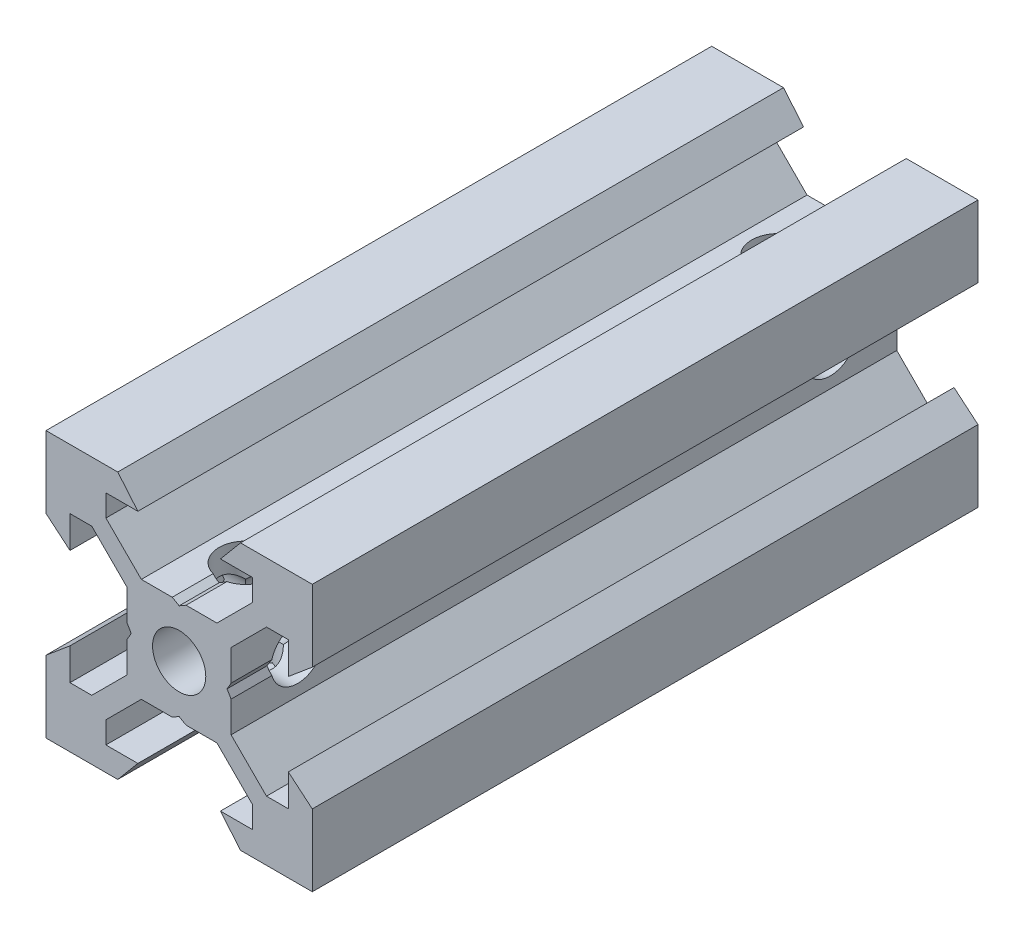
SolidWorks part; units mm, degrees
material "3.3535 (EN-AW 5754)"
ref_plane "Front Plane" through (0, 0, 0) normal (0, 0, 1) x (1, 0, 0)
ref_plane "Top Plane" through (0, 0, 0) normal (0, 1, 0) x (1, 0, 0)
ref_plane "Right Plane" through (0, 0, 0) normal (1, 0, 0) x (0, 0, -1)
sketch "Sketch1" plane through (0, 0, 0) normal (0, 0, 1) x (1, 0, 0)
  line L0 (10, 10) -> (4.6104, 10) construction
  line L1 (10, 10) -> (10, 4.6104) construction
  line L2 (10, -10) -> (10, -4.6104) construction
  line L3 (10, -10) -> (4.6104, -10) construction
  line L4 (10, 10) -> (10, 4.6104)
  line L5 (6.5607, 5.5) -> (8.2, 5.5)
  line L6 (5.5, 8.2) -> (5.5, 6.5607)
  line L7 (10, 10) -> (4.6104, 10)
  line L8 (10, 10) -> (10, 4.6104)
  line L9 (6.5607, 5.5) -> (3.9, 2.8393)
  line L10 (5.5, 6.5607) -> (2.8393, 3.9)
  line L11 (10, 4.6104) -> (8.2, 3.1)
  line L12 (4.6104, 10) -> (3.1, 8.2)
  line L13 (8.2, 3.1) -> (8.2, 5.5)
  line L14 (3.1, 8.2) -> (5.5, 8.2)
  line L15 (-6.5607, 5.5) -> (-8.2, 5.5)
  line L16 (6.5607, -5.5) -> (8.2, -5.5)
  line L17 (3.1, -8.2) -> (5.5, -8.2)
  line L18 (8.2, -3.1) -> (8.2, -5.5)
  line L19 (4.6104, -10) -> (3.1, -8.2)
  line L20 (10, -4.6104) -> (8.2, -3.1)
  line L21 (0.5196, -3.9) -> (0, -3.6)
  line L22 (0.5196, 3.9) -> (0, 3.6)
  line L23 (3.6, 0) -> (3.9, -0.5196)
  line L24 (3.9, 0.5196) -> (3.6, 0)
  line L25 (3.9, 0.5196) -> (3.9, 2.8393)
  line L26 (2.8393, 3.9) -> (0.5196, 3.9)
  line L27 (3.9, -2.8393) -> (3.9, -0.5196)
  line L28 (2.8393, -3.9) -> (0.5196, -3.9)
  line L29 (5.5, -6.5607) -> (2.8393, -3.9)
  line L30 (6.5607, -5.5) -> (3.9, -2.8393)
  line L31 (10, -10) -> (10, -4.6104)
  line L32 (10, -10) -> (4.6104, -10)
  line L33 (5.5, -8.2) -> (5.5, -6.5607)
  line L34 (-6.5607, -5.5) -> (-8.2, -5.5)
  line L35 (10, -10) -> (10, -4.6104)
  line L36 (0, 0) -> (0, 8.2) construction
  line L37 (-10, -10) -> (-4.6104, -10) construction
  line L38 (-10, -10) -> (-10, -4.6104) construction
  line L39 (-10, 10) -> (-10, 4.6104) construction
  line L40 (-10, 10) -> (-4.6104, 10) construction
  line L41 (-10, -10) -> (-10, -4.6104)
  line L43 (-5.5, -8.2) -> (-5.5, -6.5607)
  line L44 (-10, -10) -> (-4.6104, -10)
  line L45 (-10, -10) -> (-10, -4.6104)
  line L46 (-6.5607, -5.5) -> (-3.9, -2.8393)
  line L47 (-5.5, -6.5607) -> (-2.8393, -3.9)
  line L48 (-2.8393, -3.9) -> (-0.5196, -3.9)
  line L49 (-3.9, -2.8393) -> (-3.9, -0.5196)
  line L50 (-2.8393, 3.9) -> (-0.5196, 3.9)
  line L51 (-3.9, 0.5196) -> (-3.9, 2.8393)
  line L52 (-3.9, 0.5196) -> (-3.6, 0)
  line L53 (-3.6, 0) -> (-3.9, -0.5196)
  line L54 (-0.5196, 3.9) -> (0, 3.6)
  line L55 (-0.5196, -3.9) -> (0, -3.6)
  line L56 (-10, -4.6104) -> (-8.2, -3.1)
  line L57 (-4.6104, -10) -> (-3.1, -8.2)
  line L58 (-8.2, -3.1) -> (-8.2, -5.5)
  line L59 (-3.1, -8.2) -> (-5.5, -8.2)
  line L60 (-10, -10) -> (10, -10) construction
  line L61 (-10, -10) -> (-10, 10) construction
  line L62 (-3.1, 8.2) -> (-5.5, 8.2)
  line L63 (-8.2, 3.1) -> (-8.2, 5.5)
  line L64 (-4.6104, 10) -> (-3.1, 8.2)
  line L65 (-10, 4.6104) -> (-8.2, 3.1)
  line L66 (-5.5, 6.5607) -> (-2.8393, 3.9)
  line L67 (-6.5607, 5.5) -> (-3.9, 2.8393)
  line L68 (-10, 10) -> (-10, 4.6104)
  line L69 (-10, 10) -> (-4.6104, 10)
  line L70 (-5.5, 8.2) -> (-5.5, 6.5607)
  line L71 (-10, 10) -> (10, 10) construction
  line L72 (-10, 10) -> (-10, 4.6104)
  line L73 (10, -10) -> (10, 10) construction
  line L74 (-10, -10) -> (10, 10) construction
  line L75 (-10, 10) -> (10, -10) construction
  circle A0 centre (0, 0) radius 2
  dimension "D7" = 4
  dimension "D1" = 20
  dimension "D2" = 5.3896
  dimension "D3" = 4.5
  dimension "D4" = 50
  dimension "D5" = 1.8
  dimension "D6" = 1.5104
  dimension "D8" = 5.5
  dimension "D9" = 120
  dimension "D10" = 0.3
  dimension "D11" = 2.3197
  dimension "D12" = 7.8
  dimension "D13" = 7.8
  dimension "D14" = 1.5
  dimension "D15" = 2.6607
extrude "Boss-Extrude1" add sketch "Sketch1" along normal blind 50 contours L70 L62 L64 L69 L68 L65 L63 L15 L67 L51 L52 L53 L49 L46 L34 L58 L56 L41 L44 L57 L59 L43 L47 L48 L55 L21 L28 L29 L33 L17 L19 L32 L31 L20 L18 L16 L30 L27 L23 L24 L25 L9 L5 L13 L11 L4 L7 L12 L14 L6 L10
sketch "Sketch2" plane through (0, -3.9, 0) normal (0, -1, 0) x (-1, 0, 0)
  line L0 (0, -50) -> (0, -5) construction
  line L1 (0, -50) -> (0, 0) construction
  line L2 (0, 0) -> (0, -45) construction
  circle A0 centre (0, -5) radius 2
  circle A1 centre (0, -45) radius 2
  dimension "D2" = 4
  dimension "D4" = 4
  dimension "D1" = 45
  dimension "D3" = 45
extrude "Cut-Extrude1" cut sketch "Sketch2" against normal through all both and the other way through all
sketch "Sketch3" plane through (3.9, 0, 0) normal (1, 0, 0) x (0, 0, -1)
  line L0 (0, 0) -> (-45, 0) construction
  line L1 (-50, 0) -> (0, 0) construction
  line L2 (-50, 0) -> (-5, 0) construction
  circle A0 centre (-45, 0) radius 2
  circle A1 centre (-5, 0) radius 2
  dimension "D2" = 4
  dimension "D4" = 4
  dimension "D1" = 45
  dimension "D3" = 45
extrude "Cut-Extrude2" cut sketch "Sketch3" against normal through all both
